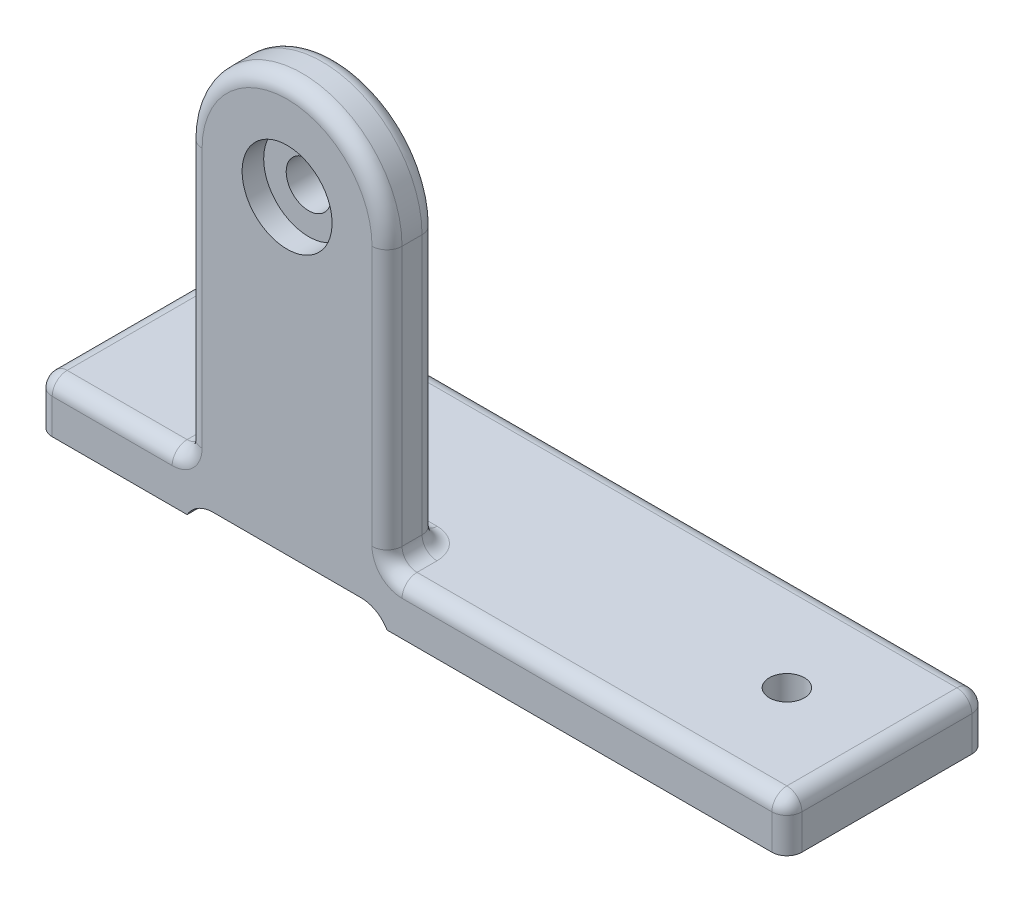
SolidWorks part; units mm, degrees
ref_plane "Front Plane" through (0, 0, 0) normal (0, 0, 1) x (1, 0, 0)
ref_plane "Top Plane" through (0, 0, 0) normal (0, 1, 0) x (1, 0, 0)
ref_plane "Right Plane" through (0, 0, 0) normal (1, 0, 0) x (0, 0, -1)
sketch "Sketch1" plane through (0, 0, 0) normal (0, 1, 0) x (1, 0, 0)
  line L1 (-75, -20) -> (75, -20)
  line L2 (-75, -20) -> (-75, 20)
  line L3 (-75, 20) -> (75, 20)
  line L4 (75, -20) -> (75, 20)
  line L5 (-75, -20) -> (75, 20) construction
  line L6 (-75, 20) -> (75, -20) construction
  point P0 (0, 0)
  dimension "D1" = 150
  dimension "D2" = 40
extrude "Boss-Extrude1" add sketch "Sketch1" along normal blind 10
sketch "Sketch2" plane through (0, 0, 20) normal (0, 0, 1) x (1, 0, 0)
  line L0 (-75, 10) -> (75, 10) construction
  line L1 (-45, 10) -> (-5, 10)
  line L2 (-45, 10) -> (-45, 65)
  line L4 (-5, 10) -> (-5, 65)
  line L5 (-75, 0) -> (75, 0) construction
  line L6 (-75, 10) -> (-75, 0) construction
  arc A0 (-45, 65) -> (-5, 65) centre (-25, 65) cw
  dimension "D2" = 20
  dimension "D1" = 65
  dimension "D3" = 50
extrude "Boss-Extrude2" add sketch "Sketch2" against normal blind 10
hole_wizard "CBORE for M6 SBHCS1" positions "Sketch5" profile "Sketch6" counterbore size "M6" standard "ANSI Metric" end condition through all
sketch "Sketch5" plane through (0, 0, 10) normal (0, 0, -1) x (-1, 0, 0)
  point P2 (25, 65)
sketch "Sketch6" plane through (-25, 65, 10) normal (1, 0, 0) x (0, 1, 0)
  line L0 (0, 0) -> (0, 10)
  line L1 (0, 10) -> (9.005, 10)
  line L3 (9.005, 10) -> (9.005, 5.68)
  line L4 (9.005, 5.68) -> (4.5, 5.68)
  line L5 (4.5, 5.68) -> (4.5, 0)
  line L7 (4.5, 0) -> (0, 0)
  line L11 (0, -6.35) -> (0, 107.95) construction
  dimension "Thru Hole Dia." = 18.01
  dimension "Thru Hole Depth" = 10
  dimension "C'Bore Dia." = 9
  dimension "C'Bore Depth" = 5.68
sketch "Sketch7" plane through (0, 0, 20) normal (0, 0, 1) x (1, 0, 0)
  line L0 (-39.8038, 3) -> (-10.1962, 3)
  line L1 (-75, 0) -> (75, 0) construction
  line L2 (-45, 0) -> (-5, 0)
  line L3 (-45, 65) -> (-45, 10) construction
  line L4 (-5, 10) -> (-5, 65) construction
  arc A0 (-39.8038, 3) -> (-45, 0) centre (-39.8038, -3) ccw
  arc A1 (-10.1962, 3) -> (-5, 0) centre (-10.1962, -3) cw
  dimension "D2" = 6
  dimension "D1" = 3
extrude "Cut-Extrude1" cut sketch "Sketch7" against normal through all
sketch "Sketch8" plane through (0, 10, 0) normal (0, 1, 0) x (1, 0, 0)
  line L0 (0, 0) -> (0, 31.8631) construction
  line L1 (-75, 20) -> (-75, -20) construction
  line L2 (75, 20) -> (-75, 20) construction
  circle A0 centre (-55, 0) radius 3.5
  circle A1 centre (55, 0) radius 3.5
  point P9 (0, 0)
  point P11 (-93.1012, 11.7982)
  dimension "D3" = 7
  dimension "D1" = 20
  dimension "D2" = 20
extrude "Cut-Extrude2" cut sketch "Sketch8" against normal through all
fillet "Fillet1" radius 3 18 edges at (-60, 10, 20) (-45, 10, 15) (35, 10, 20) (-45, 37.5, 10) (-25, 85, 10) (-45, 37.5, 20) (-25, 85, 20) (-75, 5, 20) (-75, 5, -20) (75, 5, -20) (75, 5, 20) (-75, 10, 0) (0, 10, -20) (75, 10, 0) (-5, 37.5, 10) (-5, 37.5, 20) (-5, 10, 15) (-25, 10, 10)
